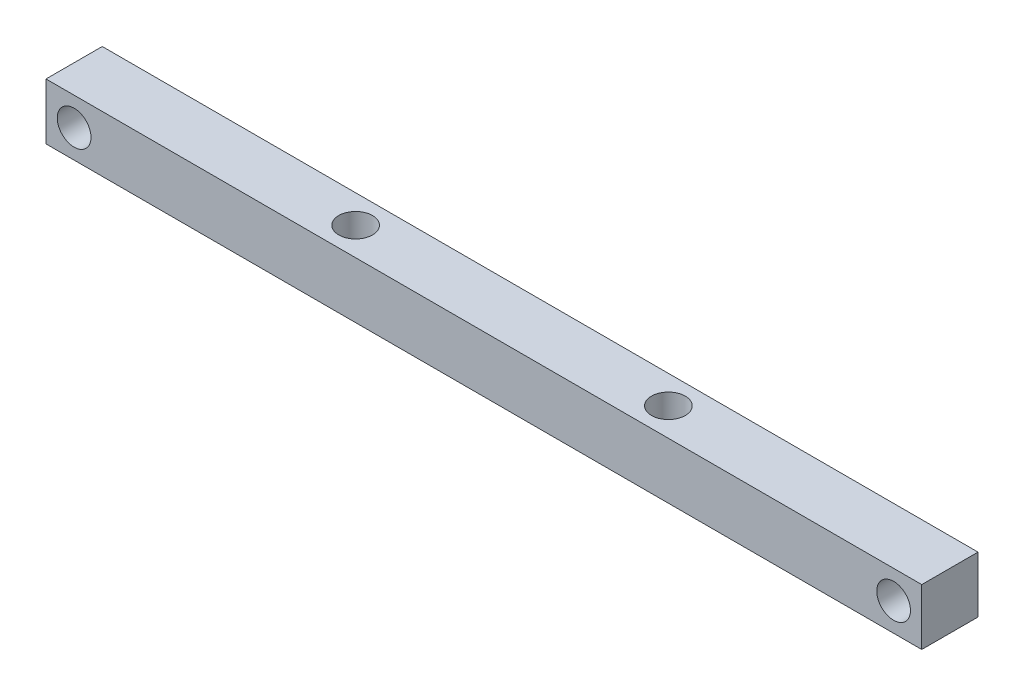
SolidWorks part; units mm, degrees
ref_plane "Front Plane" through (0, 0, 0) normal (0, 0, 1) x (1, 0, 0)
ref_plane "Top Plane" through (0, 0, 0) normal (0, 1, 0) x (1, 0, 0)
ref_plane "Right Plane" through (0, 0, 0) normal (1, 0, 0) x (0, 0, -1)
sketch "Sketch1" plane through (0, 0, 0) normal (0, 0, 1) x (1, 0, 0)
  line L1 (-103.7089, 50.8242) -> (-4.8521, 50.8242)
  line L2 (-103.7089, 50.8242) -> (-103.7089, 44.4742)
  line L3 (-103.7089, 44.4742) -> (-4.8521, 44.4742)
  line L4 (-4.8521, 50.8242) -> (-4.8521, 44.4742)
  dimension "D1" = 98.8568
  dimension "D2" = 6.35
extrude "Boss-Extrude1" add sketch "Sketch1" along normal blind 6.35
sketch "Sketch2" plane through (0, 0, 6.35) normal (0, 0, 1) x (1, 0, 0)
  line L0 (-103.7089, 47.6492) -> (-100.5339, 47.6492) construction
  line L1 (-103.7089, 50.8242) -> (-103.7089, 44.4742) construction
  line L2 (-100.5339, 47.6492) -> (-8.0271, 47.6492) construction
  line L3 (-8.0271, 47.6492) -> (-4.8521, 47.6492) construction
  line L4 (-4.8521, 44.4742) -> (-4.8521, 50.8242) construction
  line L5 (-100.5339, 44.4742) -> (-100.5339, 47.6492) construction
  line L6 (-103.7089, 44.4742) -> (-4.8521, 44.4742) construction
  line L7 (-100.5339, 47.6492) -> (-100.5339, 50.8242) construction
  line L8 (-4.8521, 50.8242) -> (-103.7089, 50.8242) construction
  circle A0 centre (-100.5339, 47.6492) radius 1.905
  circle A1 centre (-8.0271, 47.6492) radius 1.905
  dimension "D1" = 3.81
  dimension "D2" = 92.5068
extrude "Cut-Extrude1" cut sketch "Sketch2" against normal through all
sketch "Sketch3" plane through (0, 50.8242, 0) normal (0, 1, 0) x (1, 0, 0)
  line L0 (-103.7089, -3.175) -> (-71.9335, -3.175) construction
  line L1 (-103.7089, -6.35) -> (-103.7089, 0) construction
  line L2 (-71.9335, -3.175) -> (-36.6275, -3.175) construction
  line L3 (-36.6275, -3.175) -> (-4.8521, -3.175) construction
  line L4 (-4.8521, -6.35) -> (-4.8521, 0) construction
  line L5 (-71.9335, -6.35) -> (-71.9335, -3.175) construction
  line L6 (-4.8521, -6.35) -> (-103.7089, -6.35) construction
  line L7 (-71.9335, -3.175) -> (-71.9335, 0) construction
  line L8 (-4.8521, 0) -> (-103.7089, 0) construction
  circle A0 centre (-71.9335, -3.175) radius 1.905
  circle A1 centre (-36.6275, -3.175) radius 1.905
  dimension "D1" = 3.81
  dimension "D2" = 35.306
extrude "Cut-Extrude2" cut sketch "Sketch3" against normal through all
